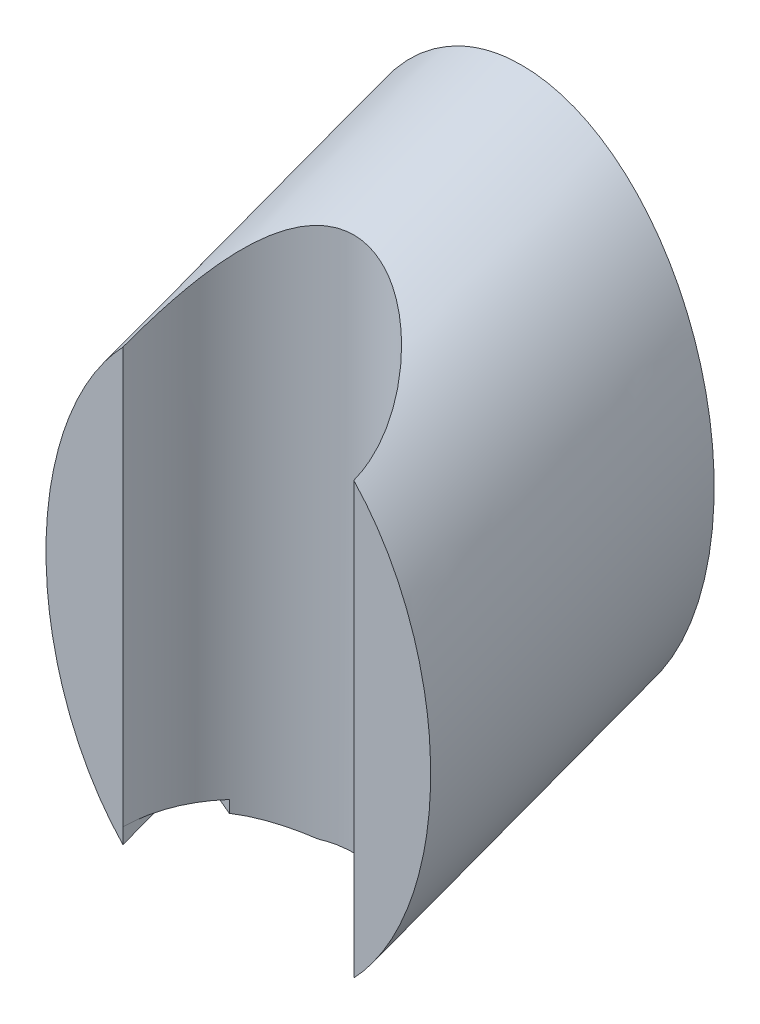
SolidWorks part; units mm, degrees
material "PE High Density"
ref_plane "Front Plane" through (0, 0, 0) normal (0, 0, 1) x (1, 0, 0)
ref_plane "Top Plane" through (0, 0, 0) normal (0, 1, 0) x (1, 0, 0)
ref_plane "Right Plane" through (0, 0, 0) normal (1, 0, 0) x (0, 0, -1)
sketch "Sketch1" plane through (0, 0, 0) normal (0, 0, 1) x (1, 0, 0)
  line L0 (-0.0815, -0.6906) -> (0.0815, -0.6906)
  ellipse E0 centre (0, 0) end of major axis (0, 0.7) minor radius 0.5 (0.0815, -0.6906) -> (-0.0815, -0.6906) ccw
  dimension "D1" = 1.4
  dimension "D2" = 1
sketch "Sketch3" plane through (0, 0, 0) normal (1, 0, 0) x (0, 0, -1)
  line L0 (0, 0) -> (0.8, 0.3)
  dimension "D1" = 0.8
  dimension "D2" = 0.3
sweep "Sweep1" add profiles "Sketch1" path "Sketch3"
sketch "Sketch5" plane through (0, 0, 0) normal (0, 1, 0) x (1, 0, 0)
  line L0 (-0.5, 0.0633) -> (-0.3, 0.0633)
  line L1 (-0.5, 0.8) -> (-0.5, 0) construction
  line L2 (0.3, 0.0633) -> (0.5, 0.0633)
  line L3 (0.5, 0) -> (0.5, 0.8) construction
  line L7 (0.5, 0.0633) -> (0.5, 0)
  line L8 (0.5, 0) -> (-0.5, 0)
  line L9 (-0.5, 0) -> (-0.5, 0.0633)
  arc A0 (-0.3, 0.0633) -> (0.3, 0.0633) centre (0, 0.0633) cw
  dimension "D1" = 0.3
extrude "Cut-Extrude1" cut sketch "Sketch5" against normal through all both and the other way through all
sketch "Sketch6" plane through (0, 0, -0.0633) normal (0, 0, 1) x (1, 0, 0)
  line L0 (0.3, -0.5363) -> (0.3, 0.5837) construction
  line L1 (-0.3, -0.5363) -> (0.3, -0.5363)
  line L2 (-0.3, -0.5363) -> (-0.3, -0.4963)
  line L3 (-0.3, -0.4963) -> (0.3, -0.4963)
  line L4 (0.3, -0.5363) -> (0.3, -0.4963)
  dimension "D1" = 0.04
extrude "Cut-Extrude2" cut sketch "Sketch6" against normal blind 0.2
